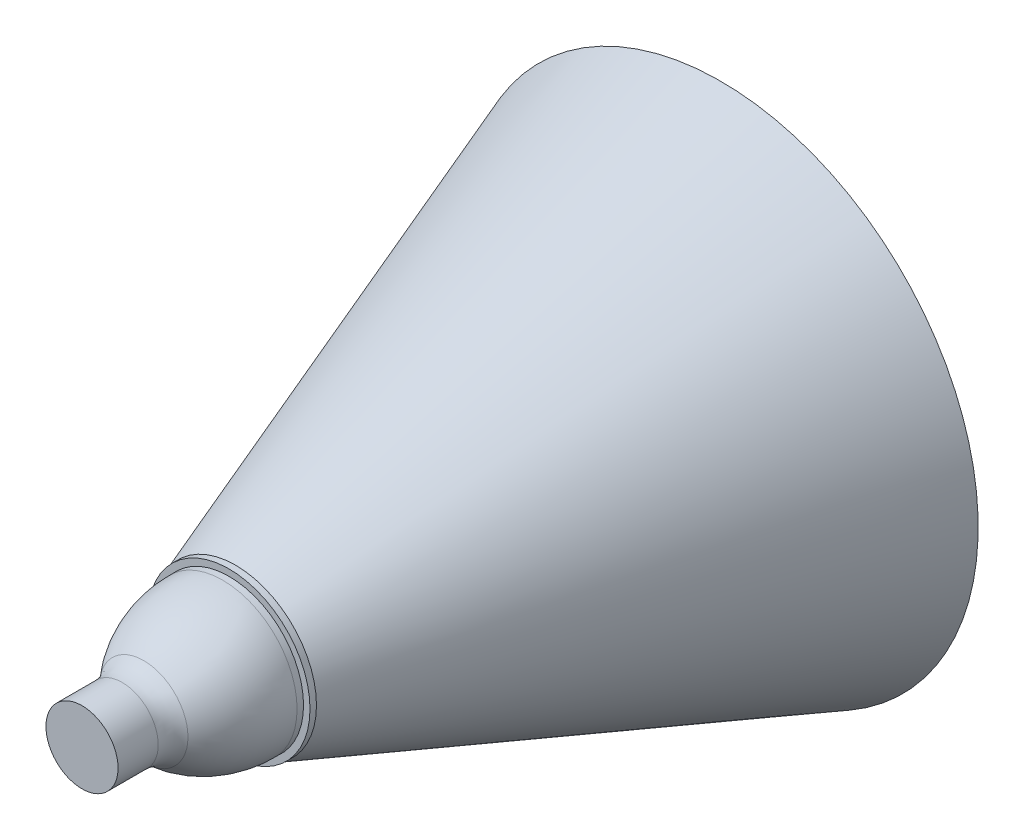
SolidWorks part; units mm, degrees
ref_plane "Front Plane" through (0, 0, 0) normal (1, 0, 0) x (0, 1, 0)
ref_plane "Top Plane" through (0, 0, 0) normal (0, 0, 1) x (0, 1, 0)
ref_plane "Right Plane" through (0, 0, 0) normal (0, 1, 0) x (-1, 0, 0)
sketch "Sketch1" plane through (0, 0, 0) normal (1, 0, 0) x (0, 1, 0)
  line L0 (0, 0) -> (-25, 0)
  line L1 (-25, 0) -> (-25, 2)
  line L2 (-25, 2) -> (-23, 2)
  line L3 (-23, 2) -> (-23, 4)
  line L4 (-11.15, 47.5) -> (-11.15, 31)
  line L5 (-11.15, 47.5) -> (0, 47.5)
  line L6 (0, -26.125) -> (0, 26.125) construction
  line L7 (0, 47.5) -> (0, 0)
  arc A0 (-11.15, 31) -> (-23, 4) centre (13.6845, 4) ccw
  dimension "D1" = 25
  dimension "D2" = 23
  dimension "D3" = 2
  dimension "D4" = 11.15
  dimension "D5" = 16.5
  dimension "D6" = 47.5
  dimension "D7" = 2
revolve "Revolve1" add sketch "Sketch1" angle 360 about L7
fillet "Fillet1" radius 10 1 edges at (11.15, 0, 31)
sketch "Sketch2" plane through (0, 0, 0) normal (1, 0, 0) x (0, 1, 0)
  line L0 (-25, 0) -> (-79.5955, -150)
  line L1 (-79.5955, -150) -> (0, -150)
  line L2 (0, 0) -> (-25, 0)
  line L3 (0, -67.5367) -> (0, 67.5367) construction
  line L4 (0, 0) -> (0, -150) construction
  line L5 (0, 0) -> (0, -150)
  dimension "D2" = 20
  dimension "D3" = 150
revolve "Revolve2" add sketch "Sketch2" angle 360 about L4
